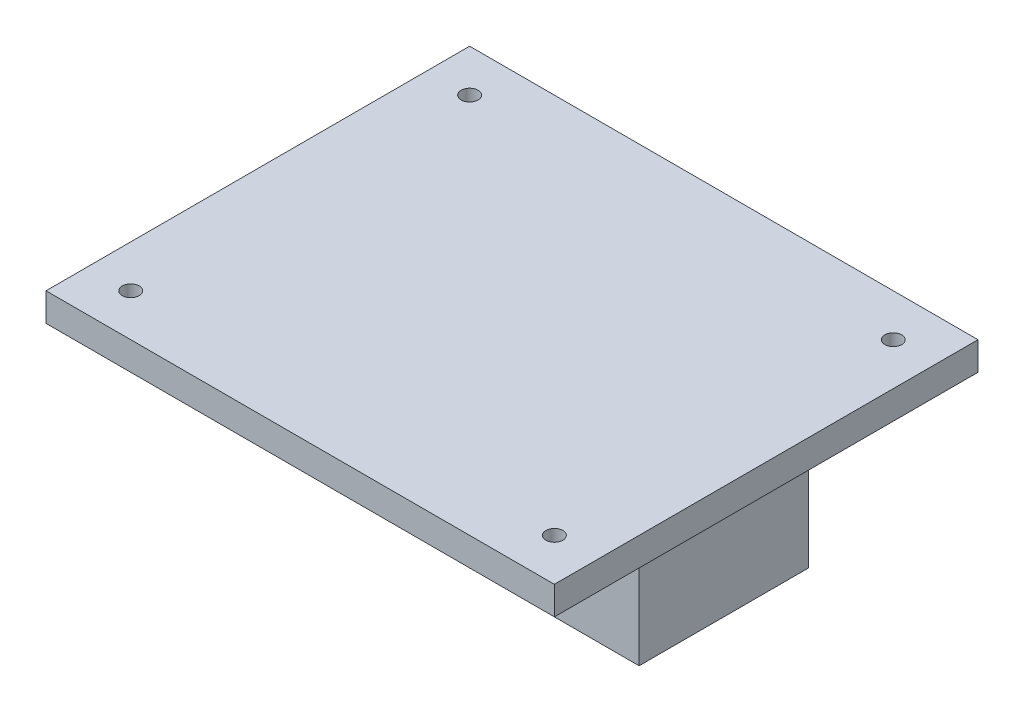
SolidWorks part; units mm, degrees
material "BUTİL"
ref_plane "Ön Düzlem" through (0, 0, 0) normal (0, 0, 1) x (1, 0, 0)
ref_plane "Üst Düzlem" through (0, 0, 0) normal (0, 1, 0) x (1, 0, 0)
ref_plane "Sağ Düzlem" through (0, 0, 0) normal (1, 0, 0) x (0, 0, -1)
sketch "Çizim1" plane through (0, 0, 0) normal (0, 1, 0) x (1, 0, 0)
  line L1 (-90, 75) -> (90, 75)
  line L2 (-90, 75) -> (-90, -75)
  line L3 (-90, -75) -> (90, -75)
  line L4 (90, 75) -> (90, -75)
  line L5 (-90, 75) -> (90, -75) construction
  line L6 (-90, -75) -> (90, 75) construction
  point P0 (0, 0)
  dimension "D1" = 180
  dimension "D2" = 150
extrude "Yükseklik-Ekstrüzyon1" add sketch "Çizim1" along normal blind 10
sketch "Çizim2" plane through (0, 10, 0) normal (0, 1, 0) x (1, 0, 0)
  line L0 (90, 75) -> (-90, 75) construction
  line L1 (-90, 75) -> (-90, -75) construction
  circle A0 centre (-75, 60) radius 3
  circle A1 centre (-75, -60) radius 3
  circle A2 centre (75, -60) radius 3
  circle A3 centre (75, 60) radius 3
  dimension "D1" = 6
  dimension "D2" = 120
  dimension "D3" = 15
  dimension "D4" = 15
  dimension "D5" = 150
extrude "Kes-Ekstrüzyon1" cut sketch "Çizim2" against normal blind 35
sketch "Çizim3" plane through (0, 0, 0) normal (0, -1, 0) x (1, 0, 0)
  line L0 (-90, -75) -> (-90, 75) construction
  line L1 (-75, 30) -> (-45, 30)
  line L2 (-75, 30) -> (-75, -30)
  line L3 (-75, -30) -> (-45, -30)
  line L4 (-45, 30) -> (-45, -30)
  line L5 (-75, 30) -> (-45, -30) construction
  line L6 (-75, -30) -> (-45, 30) construction
  line L7 (0, 82.8124) -> (0, -82.8124) construction
  line L8 (75, 30) -> (45, 30)
  line L9 (75, 30) -> (75, -30)
  line L10 (45, 30) -> (45, -30)
  line L11 (75, -30) -> (45, -30)
  point P0 (-60, 0)
  point P11 (0, 0)
  dimension "D1" = 60
  dimension "D2" = 30
  dimension "D3" = 15
extrude "Yükseklik-Ekstrüzyon2" add sketch "Çizim3" along normal blind 45
sketch "Çizim5" plane through (0, 0, -30) normal (0, 0, -1) x (-1, 0, 0)
  line L0 (75, -45) -> (45, -45) construction
  line L1 (52.5, -42) -> (67.5, -42)
  line L2 (52.5, -42) -> (52.5, -45)
  line L3 (52.5, -45) -> (67.5, -45)
  line L4 (67.5, -42) -> (67.5, -45)
  point P6 (60, -42)
  point P7 (60, -45)
  dimension "D1" = 15
  dimension "D2" = 3
extrude "Kes-Ekstrüzyon2" cut sketch "Çizim5" against normal blind 50
sketch "Çizim7" plane through (0, 0, -30) normal (0, 0, -1) x (-1, 0, 0)
  line L0 (-45, -45) -> (-75, -45) construction
  line L1 (-67.5, -42) -> (-52.5, -42)
  line L2 (-67.5, -42) -> (-67.5, -45)
  line L3 (-67.5, -45) -> (-52.5, -45)
  line L4 (-52.5, -42) -> (-52.5, -45)
  point P6 (-60, -42)
  point P7 (-60, -45)
  dimension "D1" = 3
  dimension "D2" = 15
extrude "Kes-Ekstrüzyon3" cut sketch "Çizim7" against normal blind 50
